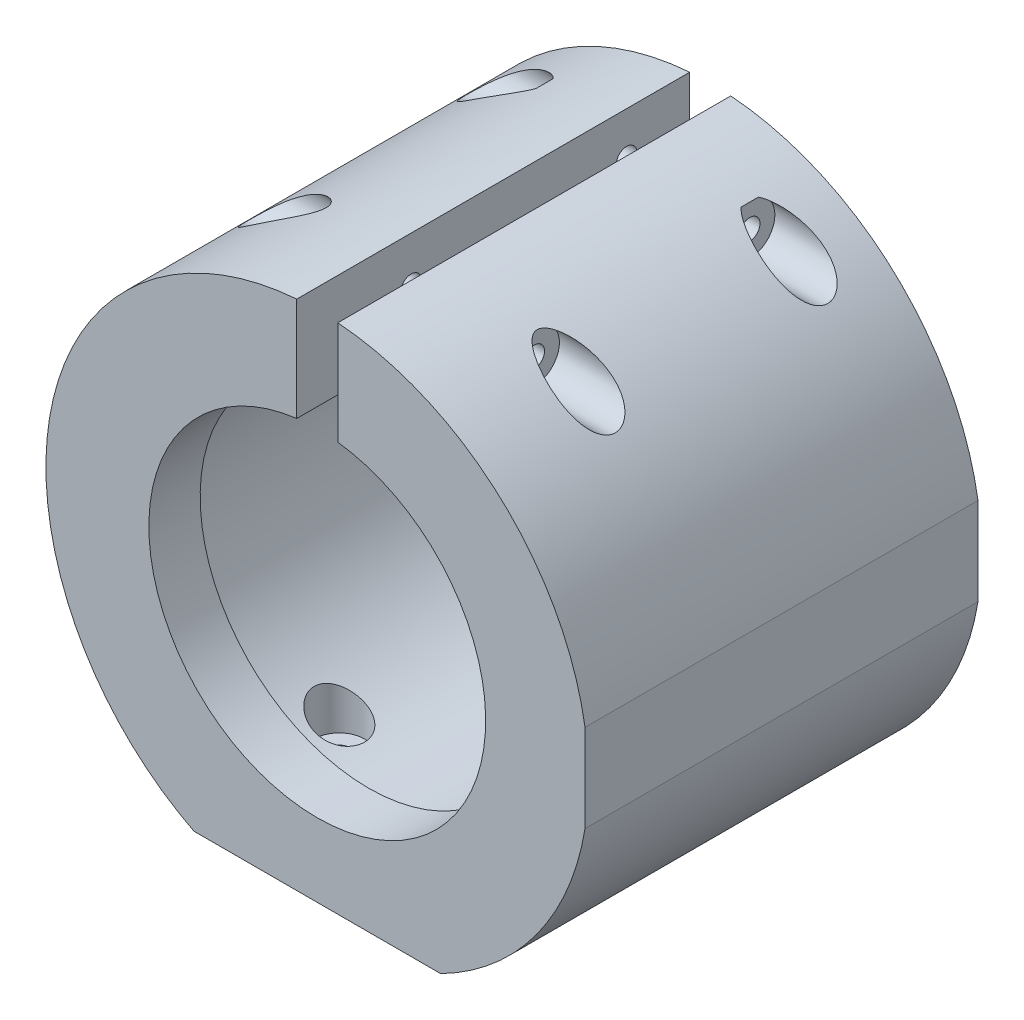
SolidWorks part; units mm, degrees
ref_plane "Front Plane" through (0, 0, 0) normal (0, 0, 1) x (1, 0, 0)
ref_plane "Top Plane" through (0, 0, 0) normal (0, 1, 0) x (1, 0, 0)
ref_plane "Right Plane" through (0, 0, 0) normal (1, 0, 0) x (0, 0, -1)
sketch "Sketch1" plane through (0, 0, 0) normal (0, 0, 1) x (1, 0, 0)
  line L0 (-12.0233, 0) -> (0, 23.5544) construction
  line L1 (-12.0233, 0) -> (12.0233, 0)
  line L4 (26.0981, 19.2811) -> (26.0981, 27.8277)
  line L5 (0, 23.5544) -> (26.0981, 19.2811) construction
  line L6 (0, 0) -> (0, 5.4544) construction
  circle A0 centre (0, 23.5544) radius 18.1
  arc A1 (12.0233, 0) -> (-12.0233, 0) centre (0, 23.5544) ccw
  dimension "D1" = 36.2
  dimension "D3" = 5.4544
  dimension "D4" = 52.8912
  dimension "D2" = 42.72
extrude "Boss-Extrude1" add sketch "Sketch1" along normal blind 33.3 contours L4 A1 L1 A0
sketch "Sketch2" plane through (0, 0, 0) normal (0, -1, 0) x (1, 0, 0)
  line L0 (-12.0233, 33.3) -> (-7.5, 28.65) construction
  line L1 (-7.5, 28.65) -> (7.5, 28.65) construction
  line L2 (7.5, 28.65) -> (12.0233, 33.3) construction
  line L3 (-12.0233, 0) -> (-7.5, 4.65) construction
  line L4 (-7.5, 4.65) -> (-7.5, 28.65) construction
  circle A0 centre (-7.5, 28.65) radius 1
  circle A1 centre (7.5, 28.65) radius 1
  circle A2 centre (-7.5, 4.65) radius 1
  circle A3 centre (7.5, 4.65) radius 1
  point P10 (0, 0)
  dimension "D1" = 2
  dimension "D2" = 15
  dimension "D3" = 24
extrude "Cut-Extrude1" cut sketch "Sketch2" against normal blind 9.3
ref_plane "Plane1" through (0, 4, 0) normal (0, -1, 0) x (-1, 0, 0)
sketch "Sketch3" plane through (0, 4, 0) normal (0, -1, 0) x (-1, 0, 0)
  circle A0 centre (-7.5, -4.65) radius 2.45
  circle A1 centre (7.5, -4.65) radius 2.45
  circle A2 centre (-7.5, -28.65) radius 2.45
  circle A3 centre (7.5, -28.65) radius 2.45
  dimension "D1" = 4.9
extrude "Cut-Extrude2" cut sketch "Sketch3" against normal blind 9.3
sketch "Sketch4" plane through (0, 0, 33.3) normal (0, 0, 1) x (1, 0, 0)
  line L0 (-2, 32.2897) -> (2, 32.2897)
  line L2 (2, 32.2897) -> (2, 61.4484)
  line L3 (2, 61.4484) -> (-2, 61.4484)
  line L4 (-2, 32.2897) -> (-2, 61.4484)
  line L5 (-2, 32.2897) -> (0, 0) construction
  line L6 (2, 61.4484) -> (1.051, 32.2897) construction
  line L7 (-3.0038, 32.2897) -> (-2, 61.4484) construction
  line L8 (-12.0233, 0) -> (12.0233, 0) construction
  line L9 (0, 0) -> (2, 32.2897) construction
  point P0 (0, 0)
  dimension "D1" = 4
extrude "Cut-Extrude3" cut sketch "Sketch4" against normal through all
sketch "Sketch5" plane through (2, 0, 0) normal (-1, 0, 0) x (0, 0, 1)
  line L0 (0, 49.9243) -> (6.15, 45.7339) construction
  line L1 (6.15, 45.7339) -> (0, 41.5436) construction
  line L2 (0, 45.7339) -> (6.15, 45.7339) construction
  line L3 (0, 41.5436) -> (0, 49.9243) construction
  line L4 (27.15, 45.466) -> (33.3, 45.466) construction
  line L5 (33.3, 41.5436) -> (33.3, 49.9243) construction
  circle A0 centre (6.15, 45.7339) radius 1
  circle A1 centre (27.15, 45.466) radius 1
  dimension "D1" = 2
  dimension "D2" = 21
extrude "Cut-Extrude4" cut sketch "Sketch5" against normal through all both and the other way through all
ref_plane "Plane2" through (10, 0, 0) normal (-1, 0, 0) x (0, 0, 1)
sketch "Sketch6" plane through (10, 0, 0) normal (-1, 0, 0) x (0, 0, 1)
  circle A0 centre (6.15, 45.7339) radius 2.45
  circle A1 centre (27.15, 45.466) radius 2.45
  dimension "D1" = 4.9
extrude "Cut-Extrude5" cut sketch "Sketch6" against normal blind 22
sketch3d "3DSketch1"
  line L0 (2, 49.9243, 33.3) -> (-2, 49.9243, 33.3)
  point P4 (0, 49.9243, 33.3)
ref_plane "Plane3" through (0, 0, 0) normal (1, 0, 0) x (0, 0, -1)
mirror "Mirror1" about plane through (0, 0, 0) normal (1, 0, 0) of "Cut-Extrude5"
sketch "Sketch7" plane through (0, 0, 33.3) normal (0, 0, -1) x (-1, 0, 0)
  line L0 (-26.0981, 19.2811) -> (-26.0981, 27.8277) construction
  line L1 (12.0233, 0) -> (-12.0233, 0) construction
  line L2 (-26.0981, 19.2811) -> (-26.0981, 27.8277)
  line L3 (12.0233, 0) -> (-12.0233, 0)
  line L5 (-2, 49.9243) -> (-2, 39.8454)
  line L6 (2, 49.9243) -> (2, 39.8454)
  arc A0 (12.0233, 0) -> (2, 49.9243) centre (0, 23.5544) ccw construction
  arc A1 (-2, 49.9243) -> (-26.0981, 27.8277) centre (0, 23.5544) ccw construction
  arc A2 (-26.0981, 19.2811) -> (-12.0233, 0) centre (0, 23.5544) ccw construction
  arc A3 (12.0233, 0) -> (2, 49.9243) centre (0, 23.5544) ccw
  arc A4 (-2, 49.9243) -> (-26.0981, 27.8277) centre (0, 23.5544) ccw
  arc A5 (-26.0981, 19.2811) -> (-12.0233, 0) centre (0, 23.5544) ccw
  arc A6 (-2, 39.8454) -> (2, 39.8454) centre (0, 23.5544) ccw
extrude "Boss-Extrude2" add sketch "Sketch7" against normal blind 5
